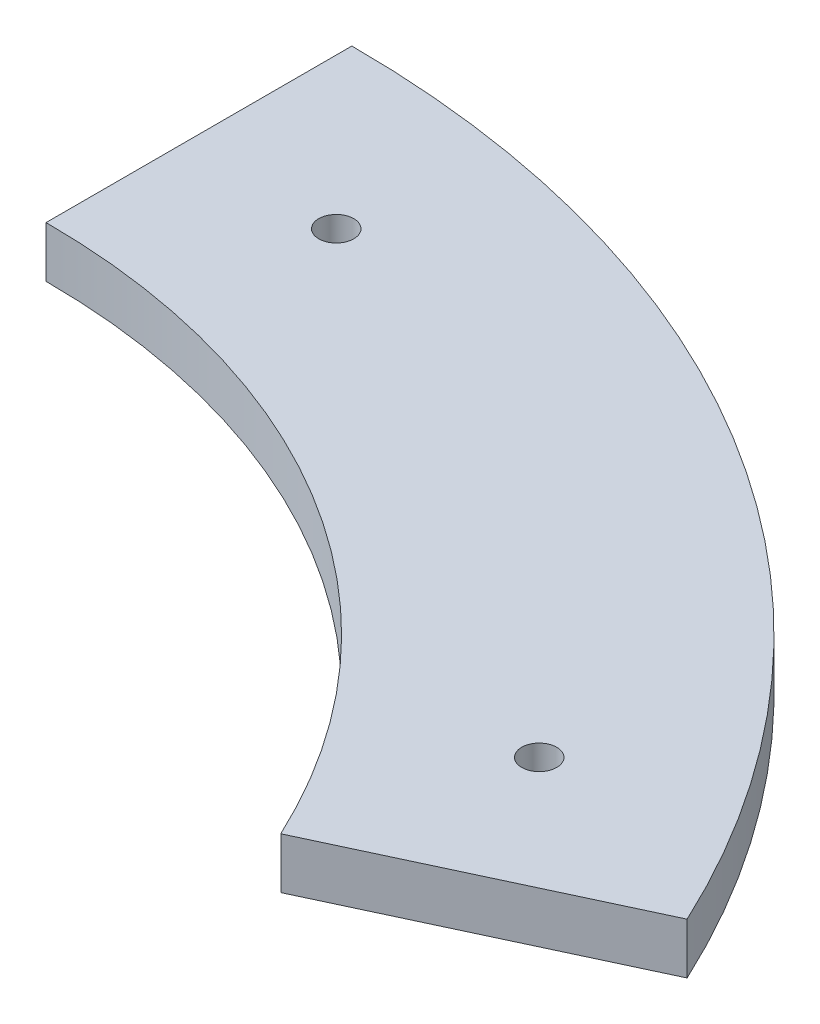
SolidWorks part; units mm, degrees
material "1023 Carbon Steel Sheet (SS)"
ref_plane "Front Plane" through (0, 0, 0) normal (0, 0, 1) x (1, 0, 0)
ref_plane "Top Plane" through (0, 0, 0) normal (0, 1, 0) x (1, 0, 0)
ref_plane "Right Plane" through (0, 0, 0) normal (1, 0, 0) x (0, 0, -1)
sketch "Sketch1" plane through (0, 0, 0) normal (0, 1, 0) x (1, 0, 0)
  line L0 (0, 177.8) -> (0, 254)
  line L2 (161.1415, 75.1415) -> (230.2022, 107.345)
  arc A0 (230.2022, 107.345) -> (0, 254) centre (0, 0) ccw
  arc A1 (161.1415, 75.1415) -> (0, 177.8) centre (0, 0) ccw
  circle A3 centre (37.4906, 212.62) radius 4.318
  circle A4 centre (176.8549, 123.8352) radius 4.318
  dimension "D1" = 76.2
  dimension "D2" = 254
  dimension "D3" = 177.8
  dimension "D4" = 8.636
  dimension "D5" = 8.636
  dimension "D6" = 215.9
  dimension "D7" = 215.9
extrude "Boss-Extrude1" add sketch "Sketch1" along normal blind 12.7 contours A1 L0 A0 L2
hole_wizard "11/32 (0.34375) Diameter Hole1" positions "Sketch6" profile "Sketch7" hole size "11/32" standard "ANSI Inch" end condition through all
sketch "Sketch6" plane through (0, 12.7, 0) normal (0, 1, 0) x (1, 0, 0)
  point P0 (37.4906, 212.62)
  point P3 (176.8549, 123.8352)
sketch "Sketch7" plane through (37.4906, 12.7, -212.62) normal (1, 0, 0) x (0, 0, 1)
  line L0 (0, 0) -> (0, 12.7)
  line L1 (0, 12.7) -> (4.3656, 12.7)
  line L2 (4.3656, 12.7) -> (4.3656, 0)
  line L5 (4.3656, 0) -> (0, 0)
  line L11 (0, -6.35) -> (0, 107.95) construction
  dimension "Thru Hole Dia." = 8.7312
  dimension "Thru Hole Depth" = 12.7
